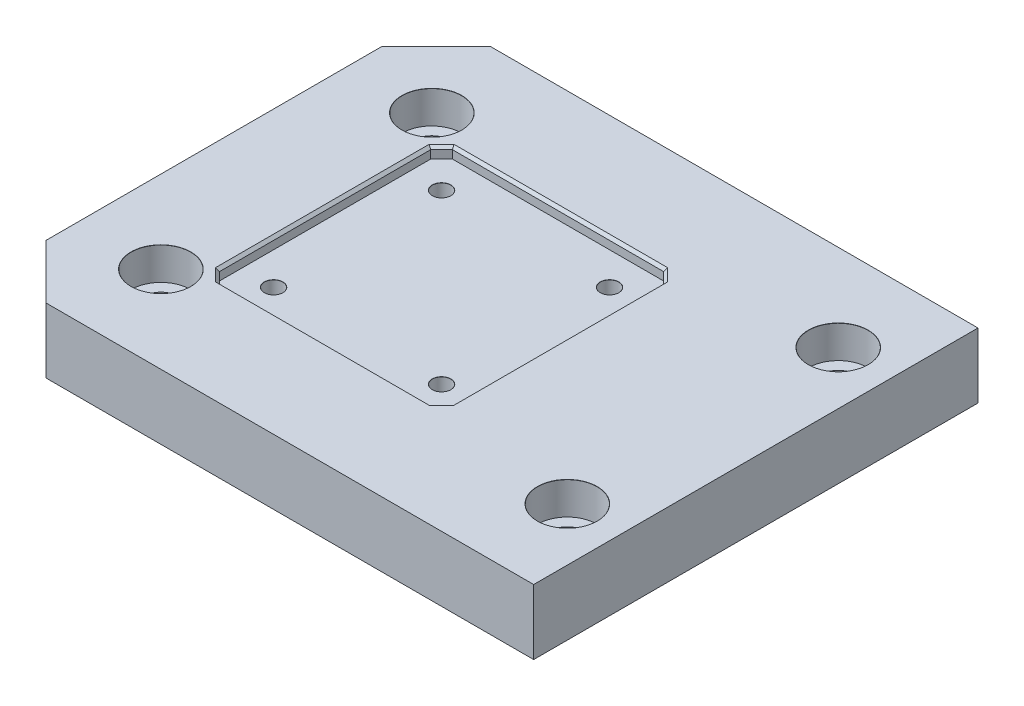
SolidWorks part; units mm, degrees
ref_plane "Front Plane" through (0, 0, 0) normal (0, 0, 1) x (1, 0, 0)
ref_plane "Top Plane" through (0, 0, 0) normal (0, 1, 0) x (1, 0, 0)
ref_plane "Right Plane" through (0, 0, 0) normal (1, 0, 0) x (0, 0, -1)
sketch "Sketch1" plane through (0, 0, 0) normal (0, 1, 0) x (1, 0, 0)
  line L0 (0, 41) -> (-42, 41)
  line L1 (-42, 41) -> (-42, -41)
  line L2 (-42, -41) -> (0, -41)
  line L3 (0, -41) -> (58, -41)
  line L4 (58, -41) -> (58, 41)
  line L5 (58, 41) -> (0, 41)
  line L6 (-42, 41) -> (58, -41) construction
  line L7 (58, 41) -> (-42, -41) construction
  point P2 (8, 0)
  point P7 (0, 0)
  dimension "D1" = 82
  dimension "D2" = 58
  dimension "D3" = 42
extrude "Boss-Extrude1" add sketch "Sketch1" along normal blind 12
sketch "Sketch2" plane through (0, 12, 0) normal (0, -1, 0) x (1, 0, 0)
  line L1 (-26.79, 25) -> (48.21, 25) construction
  line L2 (-26.79, 25) -> (-26.79, -25) construction
  line L3 (-26.79, -25) -> (48.21, -25) construction
  line L4 (48.21, 25) -> (48.21, -25) construction
  line L5 (-26.79, 25) -> (48.21, -25) construction
  line L6 (-26.79, -25) -> (48.21, 25) construction
  point P0 (23.21, -25)
  point P1 (48.21, -25)
  point P2 (10.71, 0)
  point P3 (48.21, 25)
  point P4 (23.21, 25)
  point P10 (-26.79, -25)
  point P11 (-26.79, 25)
  dimension "D1" = 48.21
  dimension "D2" = 25
  dimension "D5" = 25
  dimension "D3" = 75
  dimension "D4" = 50
hole_wizard "CBORE for M6 SHCS1" positions "Sketch13" profile "Sketch14" counterbore size "M6" standard "ANSI Metric" end condition through all
sketch "Sketch13" plane through (0, 12, 0) normal (0, 1, 0) x (1, 0, 0)
  point P6 (48.21, 25)
  point P12 (48.21, -25)
  point P15 (-26.79, -25)
  point P18 (-26.79, 25)
sketch "Sketch14" plane through (48.21, 12, -25) normal (1, 0, 0) x (0, 0, 1)
  line L0 (0, 0) -> (0, 12)
  line L1 (3.3, 11.975) -> (3.325, 12)
  line L2 (5.5, 6) -> (3.3, 6)
  line L3 (3.3, 6) -> (3.3, 11.975)
  line L5 (5.5, 6) -> (5.5, 0.025)
  line L6 (5.5, 0.025) -> (5.525, 0)
  line L7 (5.525, 0) -> (0, 0)
  line L8 (-5.5, 0.025) -> (-5.525, 0) construction
  line L11 (0, -6.35) -> (0, 107.95) construction
  line L12 (3.325, 12) -> (0, 12)
  line L13 (-3.3, 11.975) -> (-3.325, 12) construction
  dimension "Thru Hole Dia." = 6.6
  dimension "Thru Hole Depth" = 12
  dimension "C'Bore Dia." = 11
  dimension "C'Bore Depth" = 6
  dimension "Near C'Sink Dia." = 11.05
  dimension "Near C'Sink Angle" = 90
  dimension "Far C'Sink Dia." = 6.65
  dimension "Far C'Sink Angle" = 90
sketch "Sketch9" plane through (0, 12, 0) normal (0, 1, 0) x (1, 0, 0)
  line L0 (21.5, 19.5) -> (19.5, 21.5)
  line L1 (-19.5, 21.5) -> (19.5, 21.5)
  line L2 (-21.5, 19.5) -> (-21.5, -19.5)
  line L3 (-19.5, -21.5) -> (19.5, -21.5)
  line L4 (21.5, 19.5) -> (21.5, -19.5)
  line L5 (-20.5, 20.5) -> (20.5, -20.5) construction
  line L6 (-20.5, -20.5) -> (20.5, 20.5) construction
  line L7 (19.5, -21.5) -> (21.5, -19.5)
  line L8 (-21.5, -19.5) -> (-19.5, -21.5)
  line L9 (-19.5, 21.5) -> (-21.5, 19.5)
  point P0 (0, 0)
  point P17 (0, 0)
  dimension "D1" = 4
  dimension "D4" = 2
extrude "Cut-Extrude3" cut sketch "Sketch9" against normal blind 2 contours L2 L8 L3 L7 L4 L0 L1 L9
sketch "Sketch10" plane through (0, 0, 0) normal (0, 1, 0) x (1, 0, 0)
  line L1 (15.5, 15.5) -> (-15.5, 15.5) construction
  line L2 (15.5, 15.5) -> (15.5, -15.5) construction
  line L3 (15.5, -15.5) -> (-15.5, -15.5) construction
  line L4 (-15.5, 15.5) -> (-15.5, -15.5) construction
  line L5 (15.5, 15.5) -> (-15.5, -15.5) construction
  line L6 (15.5, -15.5) -> (-15.5, 15.5) construction
  point P0 (0, 0)
  point P7 (-15.5, -15.5)
  point P8 (-15.5, 15.5)
  point P9 (15.5, 15.5)
  point P10 (15.5, -15.5)
  dimension "D1" = 31
  dimension "D2" = 31
hole_wizard "CBORE for M3 SHCS1" positions "Sketch11" profile "Sketch12" counterbore size "M3" standard "ANSI Metric" end condition through all
sketch "Sketch11" plane through (0, 0, 0) normal (0, -1, 0) x (-1, 0, 0)
  point P0 (15.5, 15.5)
  point P3 (-15.5, 15.5)
  point P6 (-15.5, -15.5)
  point P9 (15.5, -15.5)
sketch "Sketch12" plane through (-15.5, 0, -15.5) normal (1, 0, 0) x (0, 0, -1)
  line L0 (0, 0) -> (0, 10)
  line L1 (1.7, 9.975) -> (1.725, 10)
  line L2 (3.25, 3) -> (1.7, 3)
  line L3 (1.7, 3) -> (1.7, 9.975)
  line L5 (3.25, 3) -> (3.25, 0.025)
  line L6 (3.25, 0.025) -> (3.275, 0)
  line L7 (3.275, 0) -> (0, 0)
  line L8 (-3.25, 0.025) -> (-3.275, 0) construction
  line L11 (0, -6.35) -> (0, 107.95) construction
  line L12 (1.725, 10) -> (0, 10)
  line L13 (-1.7, 9.975) -> (-1.725, 10) construction
  dimension "Thru Hole Dia." = 3.4
  dimension "Thru Hole Depth" = 10
  dimension "C'Bore Dia." = 6.5
  dimension "C'Bore Depth" = 3
  dimension "Near C'Sink Dia." = 6.55
  dimension "Near C'Sink Angle" = 90
  dimension "Far C'Sink Dia." = 3.45
  dimension "Far C'Sink Angle" = 90
chamfer "Chamfer1" distance 0.5 angle 45 8 edges at (20.5, 12, 20.5) (21.5, 12, 0) (20.5, 12, -20.5) (0, 12, 21.5) (-20.5, 12, 20.5) (-21.5, 12, 0) (-20.5, 12, -20.5) (0, 12, -21.5)
chamfer "Chamfer2" distance 10 angle 45 2 edges at (-42, 6, 41) (-42, 6, -41)
